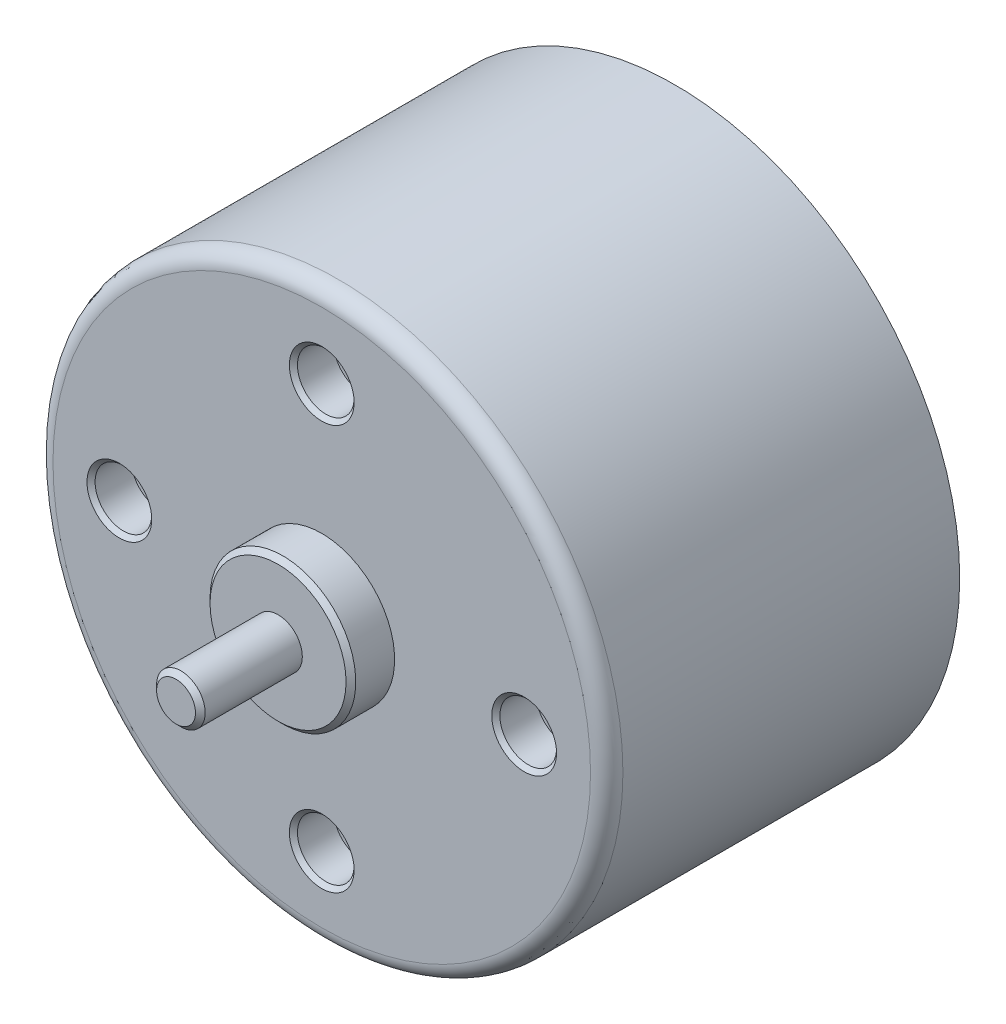
SolidWorks part; units mm, degrees
ref_plane "Front Plane" through (0, 0, 0) normal (0, 0, 1) x (1, 0, 0)
ref_plane "Top Plane" through (0, 0, 0) normal (0, 1, 0) x (1, 0, 0)
ref_plane "Right Plane" through (0, 0, 0) normal (1, 0, 0) x (0, 0, -1)
sketch "Sketch1" plane through (0, 0, 0) normal (0, 0, 1) x (1, 0, 0)
  circle A0 centre (0, 0) radius 17.6
  dimension "D1" = 35.2
extrude "Boss-Extrude1" add sketch "Sketch1" along normal blind 21.8
sketch "Sketch2" plane through (0, 0, 21.8) normal (0, 0, 1) x (1, 0, 0)
  circle A0 centre (0, 0) radius 4.5
  dimension "D1" = 9
extrude "Boss-Extrude2" add sketch "Sketch2" along normal blind 2.7
sketch "Sketch3" plane through (0, 0, 24.5) normal (0, 0, 1) x (1, 0, 0)
  circle A0 centre (0, 0) radius 1.5
  dimension "D1" = 3
extrude "Boss-Extrude3" add sketch "Sketch3" along normal blind 6.3
sketch "Sketch4" plane through (0, 0, 0) normal (0, 0, -1) x (-1, 0, 0)
  circle A0 centre (0, 0) radius 4.5 construction
  circle A3 centre (0, 0) radius 4.5
extrude "Boss-Extrude4" add sketch "Sketch4" along normal blind 2.7
sketch "Sketch5" plane through (0, 0, -2.7) normal (0, 0, -1) x (-1, 0, 0)
  circle A0 centre (0, 0) radius 1.5
  dimension "D1" = 3
extrude "Boss-Extrude5" add sketch "Sketch5" along normal blind 2.5
sketch "Sketch6" plane through (0, 0, 21.8) normal (0, 0, 1) x (1, 0, 0)
  line L0 (0, -19.36) -> (0, 19.36) construction
  line L1 (19.36, 0) -> (-19.36, 0) construction
  circle A0 centre (0, 12.5) radius 1.75
  circle A1 centre (12.5, 0) radius 1.75
  circle A2 centre (0, -12.5) radius 1.75
  circle A3 centre (-12.5, 0) radius 1.75
  point P12 (0, 0)
  dimension "D1" = 3.5
  dimension "D2" = 12.5
  dimension "D3" = 12.5
  dimension "D4" = 12.5
  dimension "D5" = 12.5
extrude "Cut-Extrude1" cut sketch "Sketch6" against normal blind 2.5
chamfer "Chamfer1" distance 0.25 4 edges at (1.75, -12.5, 21.8) (14.25, 0, 21.8) (-10.75, 0, 21.8) (1.75, 12.5, 21.8)
chamfer "Chamfer2" distance 0.3 angle 45 2 edges at (-4.5, 0, -2.7) (4.5, 0, 24.5)
fillet "Fillet1" radius 1 1 edges at (17.6, 0, 21.8)
chamfer "Chamfer3" distance 0.3 angle 45 2 edges at (1.5, 0, 30.8) (-1.5, 0, -5.2)
